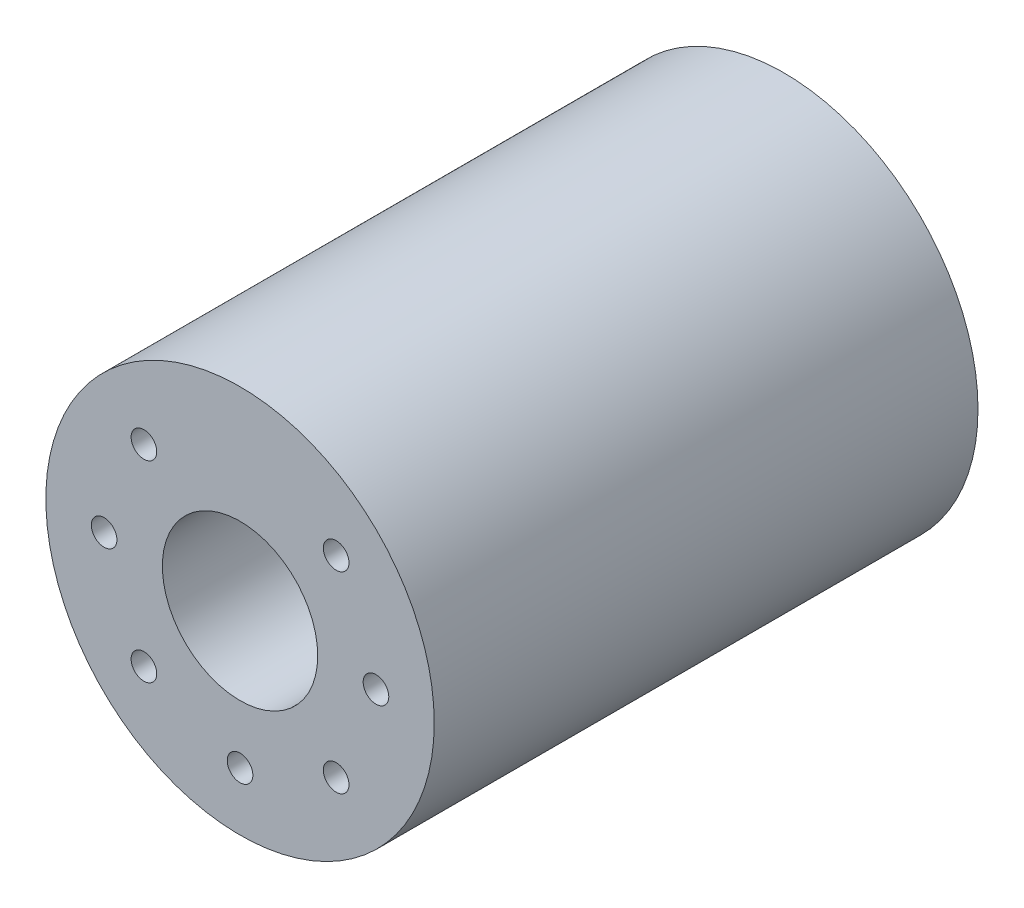
SolidWorks part; units mm, degrees
ref_plane "Front Plane" through (0, 0, 0) normal (0, 0, 1) x (1, 0, 0)
ref_plane "Top Plane" through (0, 0, 0) normal (0, 1, 0) x (1, 0, 0)
ref_plane "Right Plane" through (0, 0, 0) normal (1, 0, 0) x (0, 0, -1)
sketch "Sketch1" plane through (0, 0, 0) normal (0, 0, 1) x (1, 0, 0)
  circle A0 centre (0, 0) radius 25
  circle A1 centre (0, 0) radius 10
  dimension "D1" = 50
extrude "Boss-Extrude1" add sketch "Sketch1" along normal blind 70
sketch "Sketch3" plane through (0, 0, 70) normal (0, 0, 1) x (1, 0, 0)
  line L0 (0, 10) -> (0, 25) construction
  circle A0 centre (0, 0) radius 10 construction
  circle A1 centre (0, 0) radius 25 construction
  circle A3 centre (12.3744, 12.3744) radius 1.65
  circle A4 centre (17.5, 0) radius 1.65
  circle A5 centre (12.3744, -12.3744) radius 1.65
  circle A6 centre (0, -17.5) radius 1.65
  circle A7 centre (-12.3744, -12.3744) radius 1.65
  circle A8 centre (-17.5, 0) radius 1.65
  circle A9 centre (-12.3744, 12.3744) radius 1.65
  point P25 (0, 0)
  dimension "D1" = 3.3
  dimension "D2" = 3.3
  dimension "D3" = 3.3
  dimension "D4" = 3.3
  dimension "D5" = 3.3
  dimension "D6" = 3.3
  dimension "D7" = 3.3
extrude "Cut-Extrude1" cut sketch "Sketch3" against normal blind 20
sketch "Sketch4" plane through (0, 0, 0) normal (0, 0, -1) x (-1, 0, 0)
  line L0 (0, 10) -> (0, 25) construction
  circle A0 centre (0, 0) radius 10
  circle A2 centre (0, 17.5) radius 1.65
  circle A3 centre (12.3744, 12.3744) radius 1.65
  circle A4 centre (17.5, 0) radius 1.65
  circle A5 centre (12.3744, -12.3744) radius 1.65
  circle A6 centre (0, -17.5) radius 1.65
  circle A7 centre (-12.3744, -12.3744) radius 1.65
  circle A8 centre (-17.5, 0) radius 1.65
  circle A9 centre (-12.3744, 12.3744) radius 1.65
  point P25 (0, 0)
  dimension "D1" = 8
  dimension "D2" = 3.3
extrude "Cut-Extrude2" cut sketch "Sketch4" against normal blind 20 contours L0 A2 | A2 L0 | A3 | A4 | A5 | A6 | A7 | A8
